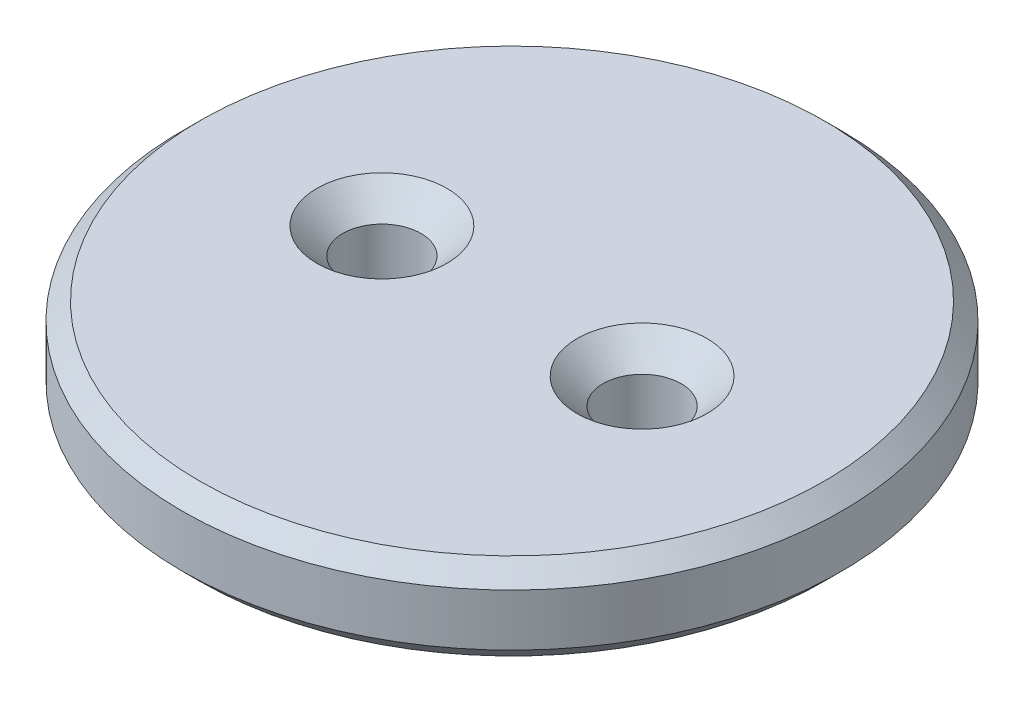
SolidWorks part; units mm, degrees
ref_plane "Front Plane" through (0, 0, 0) normal (0, 0, 1) x (1, 0, 0)
ref_plane "Top Plane" through (0, 0, 0) normal (0, 1, 0) x (1, 0, 0)
ref_plane "Right Plane" through (0, 0, 0) normal (1, 0, 0) x (0, 0, -1)
sketch "Sketch1" plane through (0, 0, 0) normal (0, 1, 0) x (1, 0, 0)
  circle A0 centre (0, 0) radius 19
  dimension "D1" = 38
extrude "Boss-Extrude1" add sketch "Sketch1" along normal blind 5
chamfer "Chamfer2" distance 1 angle 45 2 edges at (0, 0, 19) (0, 5, 19)
sketch "Sketch2" plane through (0, 5, 0) normal (0, 1, 0) x (1, 0, 0)
  line L0 (-19, 0) -> (19, 0) construction
  line L1 (0, 8.9074) -> (0, -6.7104) construction
  circle A0 centre (0, 0) radius 19 construction
  circle A1 centre (-7.5, 0) radius 2.25
  circle A2 centre (7.5, 0) radius 2.25
  dimension "D2" = 4.5
  dimension "D1" = 15
extrude "Cut-Extrude1" cut sketch "Sketch2" against normal through all
chamfer "Chamfer1" distance 1.5 angle 45 2 edges at (7.5, 5, -2.25) (-7.5, 5, 2.25)
sketch "Sketch3" plane through (0, 0, 0) normal (0, -1, 0) x (1, 0, 0)
  line L0 (7.5, 0) -> (-23.4744, 0.191) construction
  line L2 (-12.5, -6.5) -> (12.5, -6.5)
  line L3 (-12.5, -6.5) -> (-12.5, 6.5)
  line L4 (-12.5, 6.5) -> (12.5, 6.5)
  line L5 (12.5, -6.5) -> (12.5, 6.5)
  line L6 (-12.5, -6.5) -> (12.5, 6.5) construction
  line L7 (-12.5, 6.5) -> (12.5, -6.5) construction
  point P3 (0, 0)
  dimension "D1" = 13
  dimension "D2" = 25
extrude "Boss-Extrude2" add sketch "Sketch3" along normal blind 2
sketch "Sketch4" plane through (0, 0, 0) normal (0, 1, 0) x (1, 0, 0)
  circle A0 centre (7.5, 0) radius 2.25 construction
  circle A1 centre (-7.5, 0) radius 2.25 construction
  circle A2 centre (7.5, 0) radius 2.25
  circle A3 centre (-7.5, 0) radius 2.25
extrude "Cut-Extrude2" cut sketch "Sketch4" against normal through all
